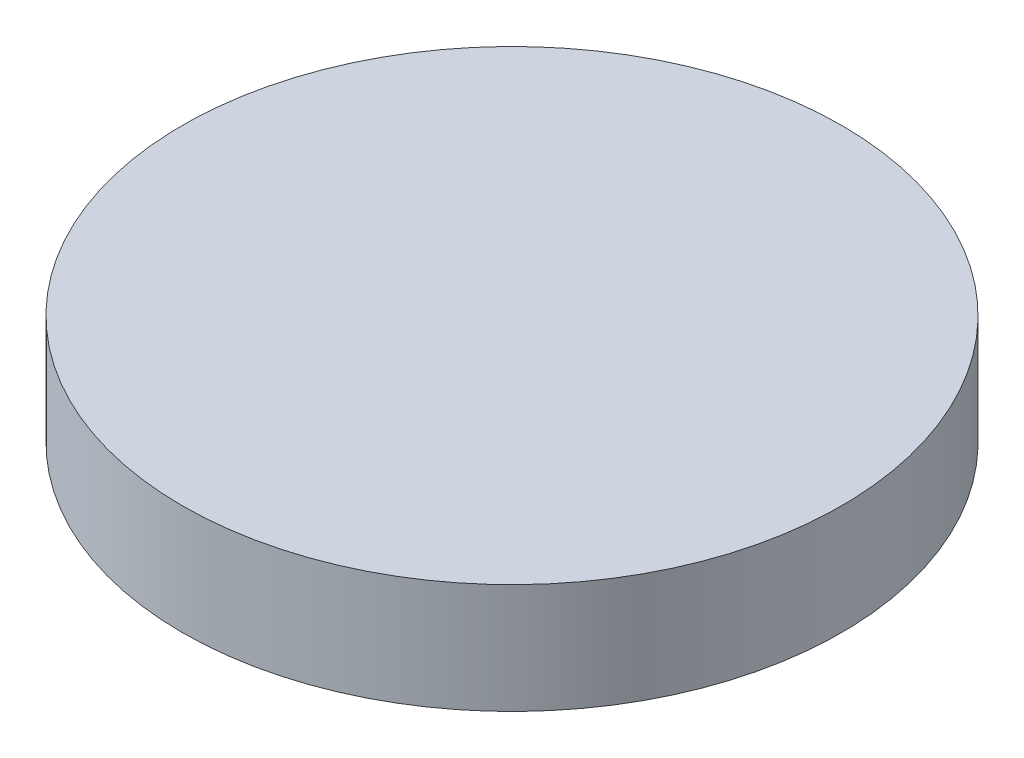
SolidWorks part; units mm, degrees
ref_plane "Front Plane" through (0, 0, 0) normal (0, 0, 1) x (1, 0, 0)
ref_plane "Top Plane" through (0, 0, 0) normal (0, 1, 0) x (1, 0, 0)
ref_plane "Right Plane" through (0, 0, 0) normal (1, 0, 0) x (0, 0, -1)
sketch "Sketch1" plane through (0, 0, 0) normal (0, 1, 0) x (1, 0, 0)
  circle A0 centre (0, 0) radius 6
extrude "Boss-Extrude1" add sketch "Sketch1" along normal blind 2
sketch "Sketch2" plane through (0, 2, 0) normal (0, 1, 0) x (1, 0, 0)
  circle A0 centre (0, 0) radius 76.2
